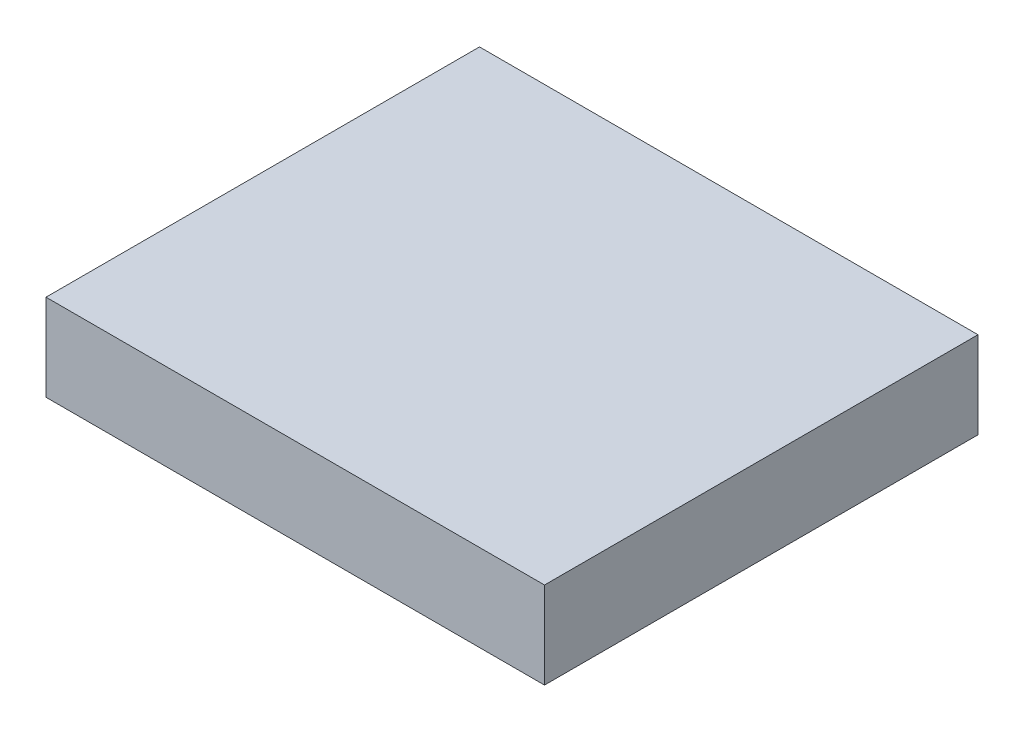
SolidWorks part; units mm, degrees
ref_plane "Front Plane" through (0, 0, 0) normal (0, 0, 1) x (1, 0, 0)
ref_plane "Top Plane" through (0, 0, 0) normal (0, 1, 0) x (1, 0, 0)
ref_plane "Right Plane" through (0, 0, 0) normal (1, 0, 0) x (0, 0, -1)
sketch "Sketch2" plane through (0, 0, 0) normal (0, 1, 0) x (1, 0, 0)
  line L1 (-5.5232, 3.45) -> (5.9768, 3.45)
  line L2 (-5.5232, 3.45) -> (-5.5232, -6.55)
  line L3 (-5.5232, -6.55) -> (5.9768, -6.55)
  line L4 (5.9768, 3.45) -> (5.9768, -6.55)
  dimension "D1" = 11.5
  dimension "D2" = 10
extrude "Boss-Extrude1" add sketch "Sketch2" along normal blind 2
scale "Scale1" scale about centroid uniform scaling yes scale factor 10
